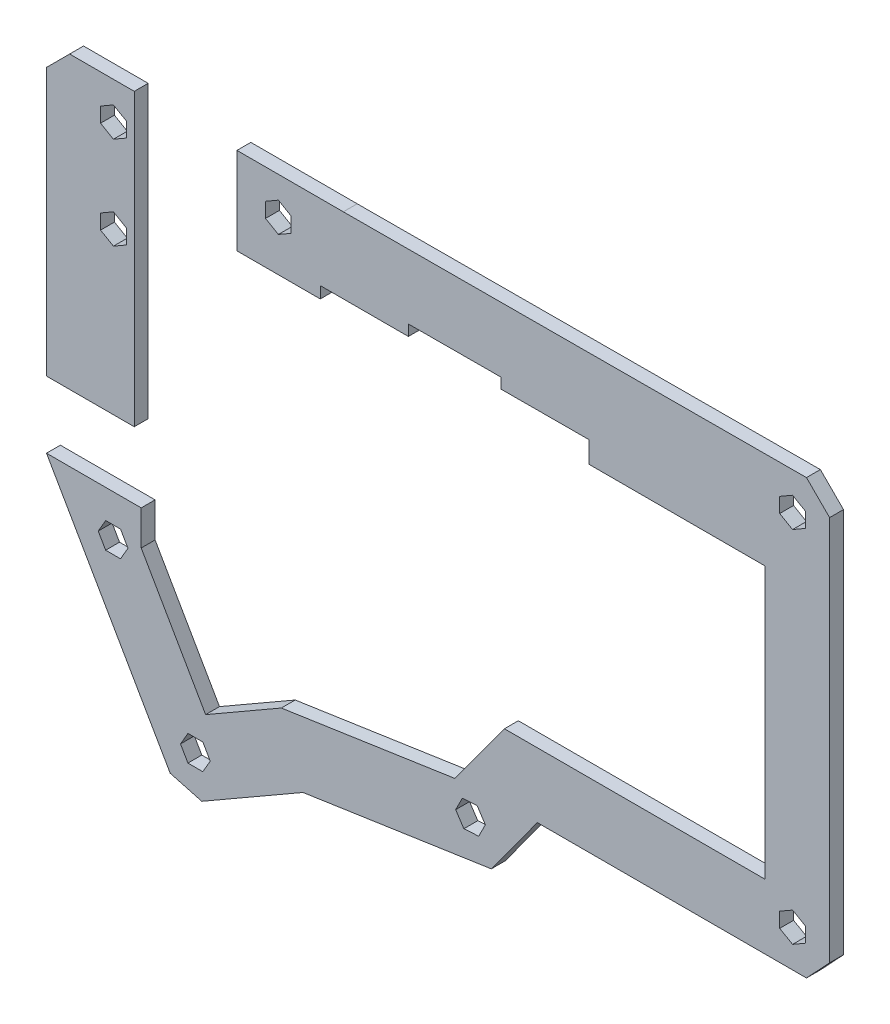
SolidWorks part; units mm, degrees
ref_plane "Plan de face" through (0, 0, 0) normal (0, 0, 1) x (1, 0, 0)
ref_plane "Plan de dessus" through (0, 0, 0) normal (0, 1, 0) x (1, 0, 0)
ref_plane "Plan de droite" through (0, 0, 0) normal (1, 0, 0) x (0, 0, -1)
sketch "Esquisse1" plane through (0, 0, 0) normal (0, 0, 1) x (1, 0, 0)
  line L0 (-117.3419, -15.4198) -> (-103.3409, -15.4198) construction
  line L1 (-103.3409, -15.4198) -> (-103.3409, -29.4208) construction
  line L2 (-103.3409, -29.4208) -> (-117.3419, -29.4208) construction
  line L3 (-117.3419, -29.4208) -> (-117.3419, -15.4198) construction
  line L4 (-98.3406, -27.0457) -> (-98.3406, -13.0447) construction
  line L5 (-98.3406, -13.0447) -> (-84.3396, -13.0447) construction
  line L6 (-84.3396, -13.0447) -> (-84.3396, -27.0457) construction
  line L7 (-84.3396, -27.0457) -> (-98.3406, -27.0457) construction
  line L8 (-79.3392, -24.6705) -> (-79.3392, -10.6695) construction
  line L9 (-79.3392, -10.6695) -> (-65.3382, -10.6695) construction
  line L10 (-65.3382, -10.6695) -> (-65.3382, -24.6705) construction
  line L11 (-65.3382, -24.6705) -> (-79.3392, -24.6705) construction
  line L12 (-60.3379, -27.0457) -> (-60.3379, -13.0447) construction
  line L13 (-60.3379, -13.0447) -> (-46.3369, -13.0447) construction
  line L14 (-46.3369, -13.0447) -> (-46.3369, -27.0457) construction
  line L15 (-46.3369, -27.0457) -> (-60.3379, -27.0457) construction
  line L16 (-41.3365, -31.796) -> (-41.3365, -17.795) construction
  line L17 (-41.3365, -17.795) -> (-27.3355, -17.795) construction
  line L18 (-27.3355, -17.795) -> (-27.3355, -31.796) construction
  line L19 (-27.3355, -31.796) -> (-41.3365, -31.796) construction
  line L20 (-22.3347, -31.796) -> (-22.3347, -17.795) construction
  line L21 (-22.3347, -17.795) -> (-8.3337, -17.795) construction
  line L22 (-8.3337, -17.795) -> (-8.3337, -31.796)
  line L23 (-8.3337, -31.796) -> (-22.3347, -31.796) construction
  line L24 (-117.3419, -34.4212) -> (-103.3409, -34.4212) construction
  line L25 (-103.3409, -34.4212) -> (-103.3409, -48.4222) construction
  line L26 (-103.3409, -48.4222) -> (-117.3419, -48.4222) construction
  line L27 (-117.3419, -48.4222) -> (-117.3419, -34.4212) construction
  line L28 (-98.3406, -32.046) -> (-84.3396, -32.046) construction
  line L29 (-84.3396, -32.046) -> (-84.3396, -46.047) construction
  line L30 (-84.3396, -46.047) -> (-98.3406, -46.047) construction
  line L31 (-98.3406, -46.047) -> (-98.3406, -32.046) construction
  line L32 (-79.3392, -29.6709) -> (-65.3382, -29.6709) construction
  line L33 (-65.3382, -29.6709) -> (-65.3382, -43.6718) construction
  line L34 (-65.3382, -43.6718) -> (-79.3392, -43.6718) construction
  line L35 (-79.3392, -43.6718) -> (-79.3392, -29.6709) construction
  line L36 (-60.3379, -32.046) -> (-46.3369, -32.046) construction
  line L37 (-46.3369, -32.046) -> (-46.3369, -46.047) construction
  line L38 (-46.3369, -46.047) -> (-60.3379, -46.047) construction
  line L39 (-60.3379, -46.047) -> (-60.3379, -32.046) construction
  line L40 (-41.3365, -36.7964) -> (-27.3355, -36.7964) construction
  line L41 (-27.3355, -36.7964) -> (-27.3355, -50.7973) construction
  line L42 (-27.3355, -50.7973) -> (-41.3365, -50.7973) construction
  line L43 (-41.3365, -50.7973) -> (-41.3365, -36.7964) construction
  line L44 (-22.3347, -36.7964) -> (-8.3337, -36.7964) construction
  line L45 (-8.3337, -36.7964) -> (-8.3337, -50.7973) construction
  line L46 (-8.3337, -50.7973) -> (-22.3347, -50.7973) construction
  line L47 (-22.3347, -50.7973) -> (-22.3347, -36.7964) construction
  line L48 (-22.3347, -55.7977) -> (-8.3337, -55.7977) construction
  line L49 (-8.3337, -55.7977) -> (-8.3337, -69.7987) construction
  line L50 (-8.3337, -69.7987) -> (-22.3347, -69.7987) construction
  line L51 (-22.3347, -69.7987) -> (-22.3347, -55.7977) construction
  line L52 (-41.3365, -55.7977) -> (-27.3355, -55.7977) construction
  line L53 (-27.3355, -55.7977) -> (-27.3355, -69.7987) construction
  line L54 (-27.3355, -69.7987) -> (-41.3365, -69.7987) construction
  line L55 (-41.3365, -69.7987) -> (-41.3365, -55.7977) construction
  line L56 (-60.3379, -51.0474) -> (-46.3369, -51.0474) construction
  line L57 (-46.3369, -51.0474) -> (-46.3369, -65.0484) construction
  line L58 (-46.3369, -65.0484) -> (-60.3379, -65.0484) construction
  line L59 (-60.3379, -65.0484) -> (-60.3379, -51.0474) construction
  line L60 (-79.3392, -48.6722) -> (-65.3382, -48.6722) construction
  line L61 (-65.3382, -48.6722) -> (-65.3382, -62.6732) construction
  line L62 (-65.3382, -62.6732) -> (-79.3392, -62.6732) construction
  line L63 (-79.3392, -62.6732) -> (-79.3392, -48.6722) construction
  line L64 (-98.3406, -51.0474) -> (-84.3396, -51.0474) construction
  line L65 (-84.3396, -51.0474) -> (-84.3396, -65.0484) construction
  line L66 (-84.3396, -65.0484) -> (-98.3406, -65.0484) construction
  line L67 (-98.3406, -65.0484) -> (-98.3406, -51.0474) construction
  line L68 (-117.3419, -53.4225) -> (-103.3409, -53.4225) construction
  line L69 (-103.3409, -53.4225) -> (-103.3409, -67.4235) construction
  line L70 (-103.3409, -67.4235) -> (-117.3419, -67.4235) construction
  line L71 (-117.3419, -67.4235) -> (-117.3419, -53.4225) construction
  line L72 (-88.8399, -70.6738) -> (-74.8389, -70.6738) construction
  line L73 (-74.8389, -70.6738) -> (-74.8389, -84.6747) construction
  line L74 (-74.8389, -84.6747) -> (-88.8399, -84.6747) construction
  line L75 (-88.8399, -84.6747) -> (-88.8399, -70.6738) construction
  line L76 (-111.4175, -75.4665) -> (-97.8899, -71.8565) construction
  line L77 (-97.8899, -71.8565) -> (-94.28, -85.3841) construction
  line L78 (-94.28, -85.3841) -> (-107.8075, -88.9941) construction
  line L79 (-107.8075, -88.9941) -> (-111.4175, -75.4665) construction
  line L80 (-134.6581, -81.5997) -> (-122.5281, -74.6075) construction
  line L81 (-122.5281, -74.6075) -> (-115.5359, -86.7375) construction
  line L82 (-115.5359, -86.7375) -> (-127.6659, -93.7297) construction
  line L83 (-127.6659, -93.7297) -> (-134.6581, -81.5997) construction
  line L86 (-6.3391, -71.9336) -> (-62.0853, -71.9336) construction
  line L89 (-72.824, -86.6446) -> (-62.0853, -71.9336) construction
  line L96 (-109.7697, -91.4639) -> (-73.0906, -86.6918) construction
  line L97 (-124.664, -99.8297) -> (-110.3971, -91.5881) construction
  line L98 (-139.9408, -76.5013) -> (-126.7151, -99.4281) construction
  line L99 (-119.8527, -15.5421) -> (-139.6028, -15.5421) construction
  line L100 (-100.8528, -13.2921) -> (-118.8527, -13.2921) construction
  line L101 (-63.8455, -8.5421) -> (-80.8528, -8.5421) construction
  line L102 (-44.8455, -10.792) -> (-62.8485, -10.792) construction
  line L103 (-25.8456, -15.5421) -> (-43.8486, -15.5421) construction
  line L104 (-6.8456, -15.5421) -> (-23.8529, -15.5421) construction
  line L105 (-6.2741, -71.3672) -> (-6.2741, -16.1136) construction
  line L106 (-23.8529, -71.9423) -> (-6.8456, -71.9423) construction
  line L107 (-61.8455, -71.9423) -> (-25.8456, -71.9423) construction
  line L108 (-72.6738, -86.4911) -> (-62.1363, -72.0583) construction
  line L109 (-140.1743, -16.1136) -> (-140.1743, -75.5958) construction
  line L110 (-134.3462, 1.5705) -> (-134.3466, -55.7217) construction
  line L111 (-134.3466, -55.7217) -> (-160.479, -70.8411) construction
  line L112 (-160.479, -70.8411) -> (-133.7613, -117.344)
  line L113 (-126.937, -119.1852) -> (-105.0783, -106.604)
  line L114 (-105.0783, -106.604) -> (-64.4097, -100.5586)
  line L115 (-64.4097, -100.5586) -> (-54.4636, -86.9336)
  line L116 (3.6609, -86.9336) -> (-54.4636, -86.9336)
  line L117 (8.6609, -81.591) -> (8.6609, 1.6823)
  line L122 (3.6609, 6.6672) -> (-96.3687, 6.3642)
  line L129 (8.6609, -86.9336) -> (8.6609, -0.337) construction
  line L130 (-48.3676, 6.5096) -> (-96.3687, 6.3642) construction
  line L131 (-115.3458, 1.5705) -> (-134.3462, 1.5705) construction
  line L132 (-160.479, -3.4295) -> (-160.479, -56.4207)
  line L134 (-119.3456, 1.5429) -> (-119.3464, -12.4295)
  line L136 (-140.0228, -78.3428) -> (-140.0228, -70.8411)
  line L138 (-160.479, -70.8411) -> (-131.2704, -121.6794) construction
  line L139 (-131.2704, -121.6794) -> (-105.0783, -106.604) construction
  line L140 (-133.7613, -117.344) -> (-126.937, -119.1852)
  line L142 (8.6609, 1.6823) -> (3.6609, 6.6672)
  line L143 (8.6609, -86.9336) -> (-54.4636, -86.9336) construction
  line L144 (8.6609, -81.591) -> (3.6609, -86.9336)
  line L147 (-103.3652, 6.3642) -> (-96.3687, 6.3642)
  line L148 (-103.3652, 6.3642) -> (-119.3456, 6.3642)
  line L149 (-119.3456, 6.3642) -> (-119.3456, 1.5429)
  line L150 (-140.0228, 1.5705) -> (-140.0228, 6.3209) construction
  line L151 (-141.5228, 6.3209) -> (-155.479, 6.3209)
  line L152 (-160.479, 1.3209) -> (-160.479, -3.4295)
  line L153 (-155.479, 6.3209) -> (-160.479, 1.3209)
  line L154 (8.6609, -1.3177) -> (-119.3458, -1.7055) construction
  line L155 (-146.0924, -79.8227) -> (-128.3223, -110.752) construction
  line L156 (-128.3223, -110.752) -> (-107.7547, -98.9139) construction
  line L157 (-140.0228, -78.3428) -> (-126.1111, -102.5565)
  line L158 (-126.1111, -102.5565) -> (-109.762, -93.1464)
  line L159 (-109.762, -93.1464) -> (-72.2631, -87.5722)
  line L160 (-72.2631, -87.5722) -> (-61.5772, -72.9336)
  line L161 (-5.3391, -72.9336) -> (-61.5772, -72.9336)
  line L162 (-5.3391, -72.9336) -> (-5.3391, -14.337)
  line L163 (-5.3391, -14.337) -> (-43.3418, -14.337)
  line L164 (-43.3418, -14.337) -> (-43.3418, -9.7225)
  line L165 (-43.3418, -9.7225) -> (-62.3174, -9.781)
  line L166 (-62.3174, -9.781) -> (-62.3244, -7.5328)
  line L167 (-62.3244, -7.5328) -> (-82.3255, -7.5934)
  line L168 (-82.3255, -7.5934) -> (-82.3183, -9.9293)
  line L169 (-82.3183, -9.9293) -> (-101.3458, -9.9293)
  line L170 (-101.3458, -9.9293) -> (-101.3458, -12.4295)
  line L171 (-101.3458, -12.4295) -> (-119.3464, -12.4295)
  line L172 (-120.3463, -12.4295) -> (-120.3466, -63.7961) construction
  line L173 (-120.3466, -63.7961) -> (-140.5236, -75.4699) construction
  line L174 (-107.7547, -98.9139) -> (-68.8973, -93.1378) construction
  line L175 (-68.8973, -93.1378) -> (-58.5285, -78.9336) construction
  line L176 (0.6609, -78.9336) -> (-58.5285, -78.9336) construction
  line L177 (0.6609, -78.9336) -> (0.6609, -1.3419) construction
  line L178 (-62.3425, -1.5328) -> (-82.3437, -1.5934) construction
  line L179 (0.6609, -78.9336) -> (0.6609, -14.337) construction
  line L180 (-160.479, -70.8411) -> (-140.0228, -70.8411)
  line L181 (-146.0228, -18.4678) -> (-148.8028, -20.0728)
  line L183 (-146.0228, -1.6779) -> (-146.0228, -21.6779) construction
  line L184 (-120.3463, -12.4295) -> (-120.3466, -64.3728) construction
  line L185 (-119.8474, -63.5072) -> (-140.5236, -75.4699) construction
  line L186 (-101.3458, -12.4295) -> (-120.3463, -12.4295) construction
  line L187 (-140.8899, -76.8336) -> (-126.1111, -102.5565) construction
  line L188 (-146.0228, -4.8879) -> (-143.2428, -3.2829)
  line L189 (-143.2428, -3.2829) -> (-143.2428, -0.0728)
  line L190 (-143.2428, -0.0728) -> (-146.0228, 1.5322)
  line L191 (-146.0228, 1.5322) -> (-148.8028, -0.0728)
  line L192 (-148.8028, -0.0728) -> (-148.8028, -3.2829)
  line L193 (-148.8028, -3.2829) -> (-146.0228, -4.8879)
  line L194 (-110.3971, -4.8884) -> (-107.6171, -3.2834)
  line L195 (-107.6171, -3.2834) -> (-107.6171, -0.0733)
  line L196 (-107.6171, -0.0733) -> (-110.3971, 1.5317)
  line L197 (-110.3971, 1.5317) -> (-113.1771, -0.0733)
  line L198 (-113.1771, -0.0733) -> (-113.1771, -3.2834)
  line L199 (-113.1771, -3.2834) -> (-110.3971, -4.8884)
  line L200 (0.6609, -4.552) -> (3.4409, -2.947)
  line L201 (3.4409, -2.947) -> (3.4409, 0.2631)
  line L202 (3.4409, 0.2631) -> (0.6609, 1.8681)
  line L203 (0.6609, 1.8681) -> (-2.1191, 0.2631)
  line L204 (-2.1191, 0.2631) -> (-2.1191, -2.947)
  line L205 (-2.1191, -2.947) -> (0.6609, -4.552)
  line L206 (0.6609, -75.7236) -> (-2.1191, -77.3286)
  line L207 (-2.1191, -77.3286) -> (-2.1191, -80.5387)
  line L208 (-2.1191, -80.5387) -> (0.6609, -82.1437)
  line L209 (0.6609, -82.1437) -> (3.4409, -80.5387)
  line L210 (3.4409, -80.5387) -> (3.4409, -77.3286)
  line L211 (3.4409, -77.3286) -> (0.6609, -75.7236)
  line L212 (-70.6661, -90.459) -> (-72.1016, -93.3302)
  line L213 (-72.1016, -93.3302) -> (-70.3329, -96.009)
  line L217 (-6.3391, -71.9336) -> (-6.3391, -15.337) construction
  line L220 (-6.3391, -15.337) -> (-44.3418, -15.337) construction
  line L221 (-44.3418, -15.337) -> (-44.3418, -10.7256) construction
  line L222 (-44.3418, -10.7256) -> (-63.3143, -10.7841) construction
  line L223 (-63.3143, -10.7841) -> (-63.3213, -8.5358) construction
  line L224 (-63.3213, -8.5358) -> (-81.3225, -8.5903) construction
  line L225 (-81.3225, -8.5903) -> (-81.3152, -10.9293) construction
  line L226 (-81.3152, -10.9293) -> (-100.3458, -10.9293) construction
  line L227 (-100.3458, -10.9293) -> (-100.3458, -13.4295) construction
  line L228 (-100.3458, -13.4295) -> (-119.3463, -13.4295) construction
  line L231 (-119.3463, -13.4295) -> (-119.3466, -64.3728) construction
  line L232 (-119.3466, -64.3728) -> (-140.0228, -76.3355) construction
  line L233 (-140.0228, -76.3355) -> (-125.7426, -101.1906) construction
  line L234 (-125.7426, -101.1906) -> (-110.0965, -92.1851) construction
  line L235 (-110.0965, -92.1851) -> (-72.824, -86.6446) construction
  line L236 (-70.3329, -96.009) -> (-67.1286, -95.8166)
  line L237 (-67.1286, -95.8166) -> (-65.693, -92.9454)
  line L238 (-65.693, -92.9454) -> (-67.4618, -90.2666)
  line L239 (-67.4618, -90.2666) -> (-70.6661, -90.459)
  line L240 (-129.9214, -107.9687) -> (-131.5323, -110.7453)
  line L241 (-131.5323, -110.7453) -> (-129.9331, -113.5286)
  line L242 (-129.9331, -113.5286) -> (-126.7231, -113.5354)
  line L243 (-126.7231, -113.5354) -> (-125.1122, -110.7588)
  line L244 (-125.1122, -110.7588) -> (-126.7114, -107.9754)
  line L245 (-126.7114, -107.9754) -> (-129.9214, -107.9687)
  line L246 (-144.4932, -82.606) -> (-142.8823, -79.8294)
  line L247 (-142.8823, -79.8294) -> (-144.4815, -77.0461)
  line L248 (-144.4815, -77.0461) -> (-147.6915, -77.0393)
  line L249 (-147.6915, -77.0393) -> (-149.3024, -79.8159)
  line L250 (-149.3024, -79.8159) -> (-147.7033, -82.5993)
  line L251 (-147.7033, -82.5993) -> (-144.4932, -82.606)
  line L252 (-148.8028, -20.0728) -> (-148.8028, -23.2829)
  line L253 (-148.8028, -23.2829) -> (-146.0228, -24.8879)
  line L254 (-146.0228, -24.8879) -> (-143.2428, -23.2829)
  line L255 (-143.2428, -23.2829) -> (-143.2428, -20.0728)
  line L256 (-143.2428, -20.0728) -> (-146.0228, -18.4678)
  line L257 (-140.0228, -53.4225) -> (-140.0228, -56.4207) construction
  line L259 (-140.0228, -56.4207) -> (-140.0228, 1.5705) construction
  line L260 (-141.5228, -56.4207) -> (-141.5228, 1.5705)
  line L261 (-141.5228, 1.5705) -> (-141.5228, 6.3209)
  line L262 (-141.5228, -56.4207) -> (-160.479, -56.4207)
  line L328 (-48.3607, 4.2621) -> (-48.3676, 6.5096) construction
  line L329 (-29.3418, 4.3208) -> (-48.3607, 4.2621) construction
  line L330 (-29.3418, -0.337) -> (-29.3418, 4.3208) construction
  line L331 (8.6609, -0.337) -> (-29.3418, -0.337) construction
  line L332 (-115.3458, 4.0707) -> (-115.3458, 1.5705) construction
  line L333 (-96.3616, 4.0707) -> (-115.3458, 4.0707) construction
  line L334 (-96.3687, 6.3642) -> (-96.3616, 4.0707) construction
  circle A2 centre (0.6609, -1.3419) radius 1.6 construction
  circle A3 centre (0.6609, -1.3419) radius 3 construction
  circle A4 centre (-110.3971, -1.6784) radius 1.6 construction
  circle A5 centre (0.6609, -78.9336) radius 1.6 construction
  circle A6 centre (-68.8973, -93.1378) radius 1.6 construction
  circle A7 centre (-128.3223, -110.752) radius 1.6 construction
  circle A8 centre (-146.0924, -79.8227) radius 1.6 construction
  circle A9 centre (-146.0228, -1.6779) radius 1.6 construction
  circle A10 centre (-146.0228, -1.6779) radius 2.78 construction
  circle A11 centre (-110.3971, -1.6784) radius 2.78 construction
  circle A12 centre (0.6609, -1.3419) radius 2.78 construction
  circle A13 centre (0.6609, -78.9336) radius 2.78 construction
  circle A14 centre (-68.8973, -93.1378) radius 2.78 construction
  circle A15 centre (-128.3223, -110.752) radius 2.78 construction
  circle A16 centre (-146.0924, -79.8227) radius 2.78 construction
  circle A17 centre (-146.0228, -21.6779) radius 2.78 construction
  point P138 (-160.479, 1.5705)
  point P139 (8.6609, 6.6823)
  point P150 (-160.479, 6.3209)
  point P197 (3.4409, -1.3419)
  dimension "D3" = 3.2
  dimension "D4" = 6
  dimension "D6" = 3.2
  dimension "D7" = 3.2
  dimension "D8" = 3.2
  dimension "D9" = 3.2
  dimension "D10" = 3.2
  dimension "D15" = 3.2
  dimension "D2" = 6
  dimension "D1" = 15
  dimension "D16" = 5.56
  dimension "D17" = 5.56
  dimension "D18" = 5.56
  dimension "D19" = 5.56
  dimension "D20" = 5.56
  dimension "D21" = 5.56
  dimension "D22" = 5.56
  dimension "D13" = 5.56
  dimension "D5" = 1
  dimension "D23" = 1.5
extrude "Boss.-Extru.1" add sketch "Esquisse1" along normal blind 3
